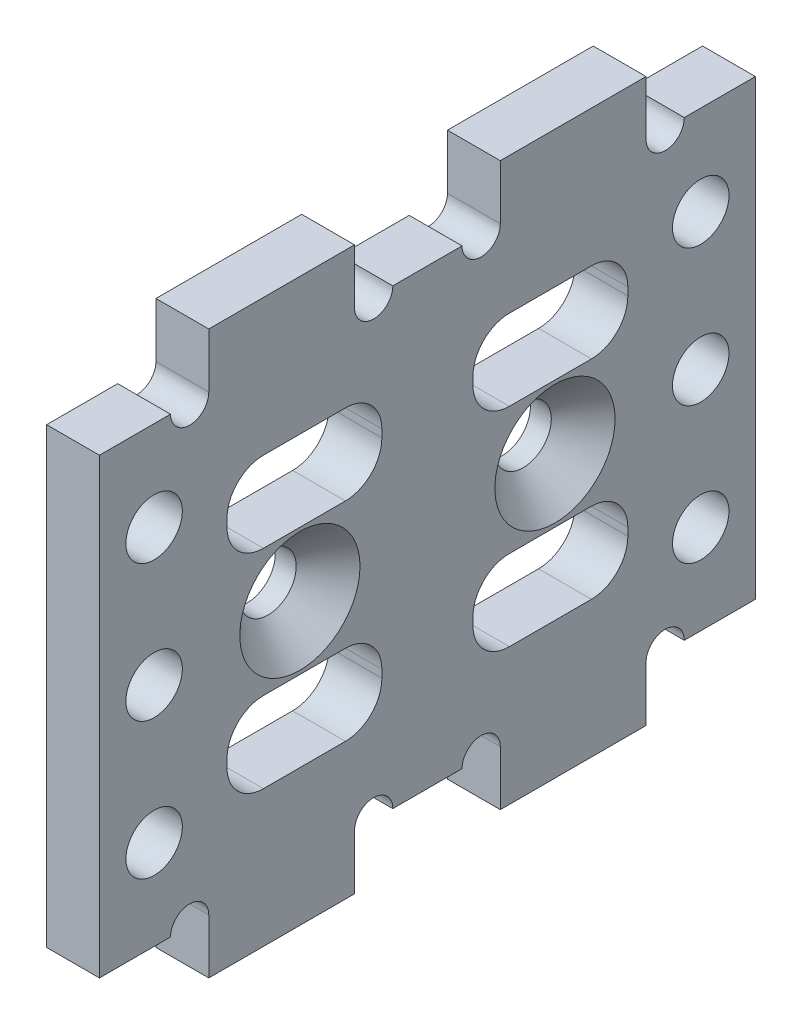
SolidWorks part; units mm, degrees
material "Thornel Mat VMA"
ref_plane "前视基准面" through (0, 0, 0) normal (0, 0, 1) x (1, 0, 0)
ref_plane "上视基准面" through (0, 0, 0) normal (0, 1, 0) x (1, 0, 0)
ref_plane "右视基准面" through (0, 0, 0) normal (1, 0, 0) x (0, 0, -1)
sketch "草图1" plane through (0, 0, 0) normal (1, 0, 0) x (0, 0, -1)
  line L0 (-12, 12.425) -> (-12, 15.425)
  line L1 (18, -12.425) -> (12, -12.425)
  line L2 (18, -12.425) -> (18, 12.425)
  line L3 (18, 12.425) -> (12, 12.425)
  line L4 (-18, -12.425) -> (-18, 12.425)
  line L5 (18, -12.425) -> (-18, 12.425) construction
  line L6 (18, 12.425) -> (-18, -12.425) construction
  line L7 (-12, 15.425) -> (-4, 15.425)
  line L8 (-4, 15.425) -> (-4, 12.425)
  line L9 (4, 12.425) -> (4, 15.425)
  line L10 (4, 15.425) -> (12, 15.425)
  line L11 (12, 15.425) -> (12, 12.425)
  line L12 (-12, 12.425) -> (-18, 12.425)
  line L13 (4, 12.425) -> (-4, 12.425)
  line L14 (0, 0) -> (10.029, 0) construction
  line L16 (12, -15.425) -> (12, -12.425)
  line L17 (4, -15.425) -> (12, -15.425)
  line L18 (4, -12.425) -> (4, -15.425)
  line L19 (-4, -15.425) -> (-4, -12.425)
  line L20 (-12, -15.425) -> (-4, -15.425)
  line L21 (-12, -12.425) -> (-12, -15.425)
  line L22 (-12, -12.425) -> (-18, -12.425)
  line L23 (4, -12.425) -> (-4, -12.425)
  circle A0 centre (-13.05, 12.425) radius 1.05
  circle A1 centre (-2.95, 12.425) radius 1.05
  circle A2 centre (2.95, 12.425) radius 1.05
  circle A3 centre (13.05, 12.425) radius 1.05
  circle A4 centre (13.05, -12.425) radius 1.05
  circle A5 centre (2.95, -12.425) radius 1.05
  circle A6 centre (-2.95, -12.425) radius 1.05
  circle A7 centre (-13.05, -12.425) radius 1.05
  point P0 (0, 0)
  dimension "D7" = 2.1
  dimension "D1" = 24.85
  dimension "D2" = 3
  dimension "D3" = 6
  dimension "D4" = 8
  dimension "D5" = 8
  dimension "D6" = 6
extrude "凸台-拉伸1" add sketch "草图1" along normal blind 2.9 contours L22 A7 L21 L20 L19 A6 L23 A5 L18 L17 L16 A4 L1 L2 L3 A3 L11 L10 L9 A2 L13 A1 L8 L7 L0 A0 L12 L4
sketch "草图2" plane through (0, 0, 0) normal (-1, 0, 0) x (0, 0, 1)
  line L0 (-18, -12.425) -> (-18, 12.425) construction
  line L1 (18, -12.425) -> (18, 12.425) construction
  line L2 (-11, 3.5) -> (-2.5, 3.5)
  line L3 (-11, -3.5) -> (-2.5, -3.5)
  line L4 (11, -7.925) -> (11, -3.5)
  line L5 (11, -7.925) -> (2.5, -7.925)
  line L7 (11, 7.925) -> (2.5, 7.925)
  line L8 (2.5, 7.925) -> (2.5, 3.5)
  line L9 (-2.5, 7.925) -> (-2.5, 3.5)
  line L10 (-2.5, 7.925) -> (-11, 7.925)
  line L12 (0, 0) -> (0, 5.5612) construction
  line L14 (-2.5, -7.925) -> (-11, -7.925)
  line L15 (-11, -7.925) -> (-11, -3.5)
  line L16 (0, 0) -> (-6.5845, 0) construction
  line L17 (-1.9, 12.425) -> (1.9, 12.425) construction
  line L18 (-11, 3.5) -> (-11, 7.925)
  line L19 (-2.5, -3.5) -> (-2.5, -7.925)
  line L20 (2.5, 3.5) -> (11, 3.5)
  line L21 (2.5, -3.5) -> (11, -3.5)
  line L22 (2.5, -3.5) -> (2.5, -7.925)
  line L23 (11, 3.5) -> (11, 7.925)
  circle A0 centre (-15, 7.5) radius 1.55
  circle A1 centre (-15, -7.5) radius 1.55
  circle A2 centre (15, 0) radius 1.55
  circle A3 centre (-15, 0) radius 1.55
  circle A4 centre (15, -7.5) radius 1.55
  circle A5 centre (15, 7.5) radius 1.55
  circle A6 centre (-7, 0) radius 1.55
  circle A7 centre (7, 0) radius 1.55
  dimension "D2" = 3.1
  dimension "D8" = 11
  dimension "D9" = 3.1
  dimension "D1" = 5
  dimension "D3" = 30
  dimension "D4" = 4
  dimension "D5" = 4.5
  dimension "D6" = 15
  dimension "D7" = 11
  dimension "D10" = 7
extrude "切除-拉伸1" cut sketch "草图2" against normal blind 10
fillet "圆角1" radius 2 16 edges at (1.45, 7.925, 2.5) (1.45, -7.925, 11) (1.45, 7.925, -2.5) (1.45, -7.925, -11) (1.45, -7.925, 2.5) (1.45, -3.5, 2.5) (1.45, -3.5, 11) (1.45, 3.5, 11) (1.45, 3.5, 2.5) (1.45, 7.925, 11) (1.45, 3.5, -2.5) (1.45, 3.5, -11) (1.45, -7.925, -2.5) (1.45, -3.5, -11) (1.45, -3.5, -2.5) (1.45, 7.925, -11)
hole_wizard "打孔尺寸(%根据十字)槽沉头木螺钉的类型1" positions "3D草图1" profile "草图3" countersink size "M3" standard "GB" end condition through all
sketch3d "3D草图1"
  line L0 (2.9, 0, 7) -> (0, 0, 7) construction
  line L1 (2.9, 0, -7) -> (0, 0, -7) construction
  point P12 (2.9, 0, 7)
  point P16 (2.9, 0, -7)
sketch "草图3" plane through (2.9, 0, 7) normal (0, 1, 0) x (0, 0, -1)
  line L0 (0, 0) -> (0, 2.9)
  line L1 (0, 2.9) -> (1.55, 2.9)
  line L2 (1.55, 2.9) -> (1.55, 1.75)
  line L3 (1.55, 1.75) -> (3.3, 0)
  line L5 (3.3, 0) -> (0, 0)
  line L6 (-1.55, 1.75) -> (-3.3, 0) construction
  line L11 (0, -6.35) -> (0, 107.95) construction
  dimension "通孔孔直径" = 3.1
  dimension "通孔孔深度" = 2.9
  dimension "近端锥形沉头孔直径" = 6.6
  dimension "近端锥形沉头孔角度" = 90
